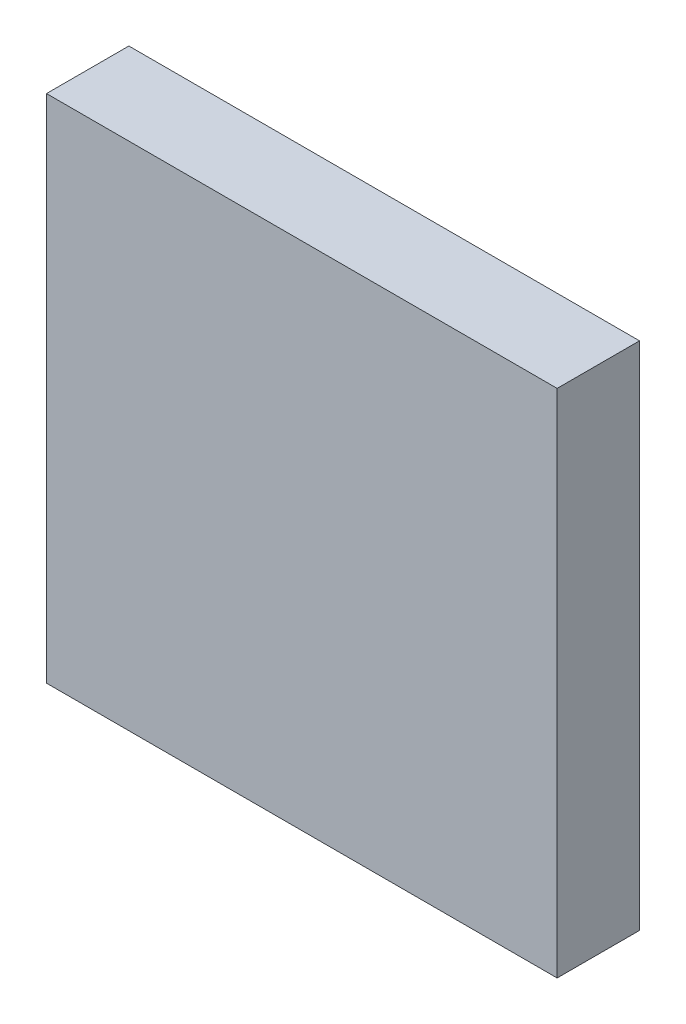
SolidWorks part; units mm, degrees
ref_plane "Спереди" through (0, 0, 0) normal (0, 0, 1) x (1, 0, 0)
ref_plane "Сверху" through (0, 0, 0) normal (0, 1, 0) x (1, 0, 0)
ref_plane "Справа" through (0, 0, 0) normal (1, 0, 0) x (0, 0, -1)
sketch "Эскиз5" plane through (0, 0, 0) normal (0, 0, 1) x (1, 0, 0)
  line L1 (-31, -31) -> (31, -31)
  line L2 (-31, -31) -> (-31, 31)
  line L3 (-31, 31) -> (31, 31)
  line L4 (31, -31) -> (31, 31)
  line L5 (-31, -31) -> (31, 31) construction
  line L6 (-31, 31) -> (31, -31) construction
  point P0 (0, 0)
extrude "Бобышка-Вытянуть2" add sketch "Эскиз5" along normal blind 10 contours L2 L3 L4 L1
sketch "Эскиз13" plane through (0, 0, 10) normal (0, 0, 1) x (1, 0, 0)
  line L0 (-8.5, 3.8388) -> (-8.5, -2.9703)
  line L1 (8.5, -2.9278) -> (8.5, 3.8388)
  spline S0 degree 3 poles (-3.7602, -6.2881) (-4.1456, -5.7125) (-4.7609, -5.3316) (-5.448, -5.2431) knots 0 0 0 0 0.333333 0.333333 0.333333 0.333333
  spline S1 degree 3 poles (-5.448, -5.2431) (-6.135, -5.1547) (-6.8268, -5.3675) (-7.3454, -5.8267) knots 0.333333 0.333333 0.333333 0.333333 1 1 1 1
  spline S2 degree 3 poles (-8.2703, 4.2595) (-8.4134, 4.1675) (-8.5, 4.009) (-8.5, 3.8388) knots 0 0 0 0 1 1 1 1
  spline S3 degree 3 poles (8.2703, 4.2595) (3.2319, 7.4966) (-3.2319, 7.4966) (-8.2703, 4.2595) knots 0 0 0 0 1 1 1 1
  spline S4 degree 3 poles (8.5, 3.8388) (8.5, 4.009) (8.4134, 4.1675) (8.2703, 4.2595) knots 0 0 0 0 1 1 1 1
  spline S5 degree 3 poles (-8.9672, -4.0581) (-8.6689, -3.7749) (-8.5, -3.3816) (-8.5, -2.9703) knots 0 0 0 0 1 1 1 1
  spline S6 degree 3 poles (-8.9672, -4.0581) (-9.4419, -4.5088) (-9.4678, -5.2568) (-9.0253, -5.7393) knots 0 0 0 0 0.333333 0.333333 0.333333 0.333333
  spline S7 degree 3 poles (-9.0253, -5.7393) (-8.5829, -6.2218) (-7.8355, -6.2607) (-7.3454, -5.8267) knots 0.333333 0.333333 0.333333 0.333333 1 1 1 1
  spline S8 degree 3 poles (8.5, -2.9278) (8.5, -3.3579) (8.6732, -3.77) (8.9805, -4.0709) knots 0 0 0 0 1 1 1 1
  spline S9 degree 3 poles (7.6987, -6.0438) (6.4648, -5.5547) (5.0779, -5.6352) (3.9089, -6.2639) knots 0 0 0 0 1 1 1 1
  spline S10 degree 3 poles (7.6987, -6.0438) (8.2299, -6.2544) (8.8358, -6.0612) (9.1472, -5.5821) knots 0 0 0 0 0.333333 0.333333 0.333333 0.333333
  spline S11 degree 3 poles (9.1472, -5.5821) (9.4585, -5.1029) (9.3888, -4.4707) (8.9805, -4.0709) knots 0.333333 0.333333 0.333333 0.333333 1 1 1 1
  spline S12 degree 3 poles (3.1792, -6.3186) (1.2825, -5.6394) (-0.8063, -5.741) (-2.6281, -6.6012) knots 0 0 0 0 1 1 1 1
  spline S13 degree 3 poles (-3.7602, -6.2881) (-3.5123, -6.6582) (-3.0309, -6.7914) (-2.6281, -6.6012) knots 0 0 0 0 1 1 1 1
  spline S14 degree 3 poles (3.1792, -6.3186) (3.4192, -6.4045) (3.6844, -6.3847) (3.9089, -6.2639) knots 0 0 0 0 1 1 1 1
sketch "Эскиз15" plane through (0, 0, 10) normal (0, 0, 1) x (1, 0, 0)
  line L0 (-8.5, 3.8389) -> (-8.5, -2.9702)
  line L1 (8.5, -2.9277) -> (8.5, 3.8389)
  line L2 (-12.5, -12.5) -> (12.5, -12.5)
  line L3 (12.5, -12.5) -> (12.5, 12.5)
  line L4 (12.5, 12.5) -> (-12.5, 12.5)
  line L5 (-12.5, 12.5) -> (-12.5, -12.5)
  spline S0 degree 3 poles (8, 2.6874) (8, 2.9636) (7.7761, 3.1874) (7.5, 3.1874) knots 0 0 0 0 0.2 0.2 0.2 0.2
  spline S1 degree 3 poles (7.5, 3.1874) (7.2239, 3.1874) (7, 2.9636) (7, 2.6874) knots 0.2 0.2 0.2 0.2 0.4 0.4 0.4 0.4
  spline S2 degree 3 poles (7, 2.6874) (7, 2.4113) (7.2239, 2.1874) (7.5, 2.1874) knots 0.4 0.4 0.4 0.4 0.6 0.6 0.6 0.6
  spline S3 degree 3 poles (7.5, 2.1874) (7.7761, 2.1874) (8, 2.4113) (8, 2.6874) knots 0.6 0.6 0.6 0.6 1 1 1 1
  spline S4 degree 3 poles (-4.6079, 1.1218) (-4.6079, 1.6188) (-5.0108, 2.0218) (-5.5079, 2.0218) knots 0 0 0 0 0.2 0.2 0.2 0.2
  spline S5 degree 3 poles (-5.5079, 2.0218) (-6.0049, 2.0218) (-6.4079, 1.6188) (-6.4079, 1.1218) knots 0.2 0.2 0.2 0.2 0.4 0.4 0.4 0.4
  spline S6 degree 3 poles (-6.4079, 1.1218) (-6.4079, 0.6247) (-6.0049, 0.2218) (-5.5079, 0.2218) knots 0.4 0.4 0.4 0.4 0.6 0.6 0.6 0.6
  spline S7 degree 3 poles (-5.5079, 0.2218) (-5.0108, 0.2218) (-4.6079, 0.6247) (-4.6079, 1.1218) knots 0.6 0.6 0.6 0.6 1 1 1 1
  spline S8 degree 3 poles (7.0549, -0.2908) (7.0549, 0.2063) (6.652, 0.6092) (6.1549, 0.6092) knots 0 0 0 0 0.2 0.2 0.2 0.2
  spline S9 degree 3 poles (6.1549, 0.6092) (5.6579, 0.6092) (5.2549, 0.2063) (5.2549, -0.2908) knots 0.2 0.2 0.2 0.2 0.4 0.4 0.4 0.4
  spline S10 degree 3 poles (5.2549, -0.2908) (5.2549, -0.7878) (5.6579, -1.1908) (6.1549, -1.1908) knots 0.4 0.4 0.4 0.4 0.6 0.6 0.6 0.6
  spline S11 degree 3 poles (6.1549, -1.1908) (6.652, -1.1908) (7.0549, -0.7878) (7.0549, -0.2908) knots 0.6 0.6 0.6 0.6 1 1 1 1
  spline S12 degree 3 poles (-7, 2.6874) (-7, 2.9636) (-7.2239, 3.1874) (-7.5, 3.1874) knots 0 0 0 0 0.2 0.2 0.2 0.2
  spline S13 degree 3 poles (-7.5, 3.1874) (-7.7761, 3.1874) (-8, 2.9636) (-8, 2.6874) knots 0.2 0.2 0.2 0.2 0.4 0.4 0.4 0.4
  spline S14 degree 3 poles (-8, 2.6874) (-8, 2.4113) (-7.7761, 2.1874) (-7.5, 2.1874) knots 0.4 0.4 0.4 0.4 0.6 0.6 0.6 0.6
  spline S15 degree 3 poles (-7.5, 2.1874) (-7.2239, 2.1874) (-7, 2.4113) (-7, 2.6874) knots 0.6 0.6 0.6 0.6 1 1 1 1
  spline S16 degree 3 poles (-7.5909, -4.9282) (-7.5909, -4.6244) (-7.8371, -4.3782) (-8.1409, -4.3782) knots 0 0 0 0 0.2 0.2 0.2 0.2
  spline S17 degree 3 poles (-8.1409, -4.3782) (-8.4447, -4.3782) (-8.6909, -4.6244) (-8.6909, -4.9282) knots 0.2 0.2 0.2 0.2 0.4 0.4 0.4 0.4
  spline S18 degree 3 poles (-8.6909, -4.9282) (-8.6909, -5.2319) (-8.4447, -5.4782) (-8.1409, -5.4782) knots 0.4 0.4 0.4 0.4 0.6 0.6 0.6 0.6
  spline S19 degree 3 poles (-8.1409, -5.4782) (-7.8371, -5.4782) (-7.5909, -5.2319) (-7.5909, -4.9282) knots 0.6 0.6 0.6 0.6 1 1 1 1
  spline S20 degree 3 poles (8.6909, -4.9282) (8.6909, -4.6244) (8.4447, -4.3782) (8.1409, -4.3782) knots 0 0 0 0 0.2 0.2 0.2 0.2
  spline S21 degree 3 poles (8.1409, -4.3782) (7.8371, -4.3782) (7.5909, -4.6244) (7.5909, -4.9282) knots 0.2 0.2 0.2 0.2 0.4 0.4 0.4 0.4
  spline S22 degree 3 poles (7.5909, -4.9282) (7.5909, -5.2319) (7.8371, -5.4782) (8.1409, -5.4782) knots 0.4 0.4 0.4 0.4 0.6 0.6 0.6 0.6
  spline S23 degree 3 poles (8.1409, -5.4782) (8.4447, -5.4782) (8.6909, -5.2319) (8.6909, -4.9282) knots 0.6 0.6 0.6 0.6 1 1 1 1
  spline S24 degree 3 poles (3.9826, -5.4712) (3.9826, -5.195) (3.7587, -4.9712) (3.4826, -4.9712) knots 0 0 0 0 0.2 0.2 0.2 0.2
  spline S25 degree 3 poles (3.4826, -4.9712) (3.2064, -4.9712) (2.9826, -5.195) (2.9826, -5.4712) knots 0.2 0.2 0.2 0.2 0.4 0.4 0.4 0.4
  spline S26 degree 3 poles (2.9826, -5.4712) (2.9826, -5.7473) (3.2064, -5.9712) (3.4826, -5.9712) knots 0.4 0.4 0.4 0.4 0.6 0.6 0.6 0.6
  spline S27 degree 3 poles (3.4826, -5.9712) (3.7587, -5.9712) (3.9826, -5.7473) (3.9826, -5.4712) knots 0.6 0.6 0.6 0.6 1 1 1 1
  spline S28 degree 3 poles (-2.5123, -5.7872) (-2.5123, -5.5111) (-2.7362, -5.2872) (-3.0123, -5.2872) knots 0 0 0 0 0.2 0.2 0.2 0.2
  spline S29 degree 3 poles (-3.0123, -5.2872) (-3.2885, -5.2872) (-3.5123, -5.5111) (-3.5123, -5.7872) knots 0.2 0.2 0.2 0.2 0.4 0.4 0.4 0.4
  spline S30 degree 3 poles (-3.5123, -5.7872) (-3.5123, -6.0634) (-3.2885, -6.2872) (-3.0123, -6.2872) knots 0.4 0.4 0.4 0.4 0.6 0.6 0.6 0.6
  spline S31 degree 3 poles (-3.0123, -6.2872) (-2.7362, -6.2872) (-2.5123, -6.0634) (-2.5123, -5.7872) knots 0.6 0.6 0.6 0.6 1 1 1 1
  spline S32 degree 3 poles (6.6049, -0.2908) (6.6049, -0.0422) (6.4034, 0.1592) (6.1549, 0.1592) knots 0 0 0 0 0.2 0.2 0.2 0.2
  spline S33 degree 3 poles (6.1549, 0.1592) (5.9064, 0.1592) (5.7049, -0.0422) (5.7049, -0.2908) knots 0.2 0.2 0.2 0.2 0.4 0.4 0.4 0.4
  spline S34 degree 3 poles (5.7049, -0.2908) (5.7049, -0.5393) (5.9064, -0.7408) (6.1549, -0.7408) knots 0.4 0.4 0.4 0.4 0.6 0.6 0.6 0.6
  spline S35 degree 3 poles (6.1549, -0.7408) (6.4034, -0.7408) (6.6049, -0.5393) (6.6049, -0.2908) knots 0.6 0.6 0.6 0.6 1 1 1 1
  spline S36 degree 3 poles (-5.0579, 1.1218) (-5.0579, 1.3703) (-5.2594, 1.5718) (-5.5079, 1.5718) knots 0 0 0 0 0.2 0.2 0.2 0.2
  spline S37 degree 3 poles (-5.5079, 1.5718) (-5.7564, 1.5718) (-5.9579, 1.3703) (-5.9579, 1.1218) knots 0.2 0.2 0.2 0.2 0.4 0.4 0.4 0.4
  spline S38 degree 3 poles (-5.9579, 1.1218) (-5.9579, 0.8733) (-5.7564, 0.6718) (-5.5079, 0.6718) knots 0.4 0.4 0.4 0.4 0.6 0.6 0.6 0.6
  spline S39 degree 3 poles (-5.5079, 0.6718) (-5.2594, 0.6718) (-5.0579, 0.8733) (-5.0579, 1.1218) knots 0.6 0.6 0.6 0.6 1 1 1 1
  spline S40 degree 3 poles (5.7898, -5.6368) (5.8728, -5.6949) (5.9715, -5.7264) (6.0728, -5.7271) knots 0 0 0 0 1 1 1 1
  spline S41 degree 3 poles (-5.4083, -5.2485) (-5.2964, -5.2648) (-5.1822, -5.2427) (-5.0845, -5.1857) knots 0 0 0 0 1 1 1 1
  spline S42 degree 3 poles (-3.7602, -6.288) (-4.1456, -5.7124) (-4.7609, -5.3315) (-5.448, -5.243) knots 0 0 0 0 0.333333 0.333333 0.333333 0.333333
  spline S43 degree 3 poles (-5.448, -5.243) (-6.135, -5.1546) (-6.8268, -5.3674) (-7.3454, -5.8266) knots 0.333333 0.333333 0.333333 0.333333 1 1 1 1
  spline S44 degree 3 poles (-8.2703, 4.2596) (-8.4134, 4.1676) (-8.5, 4.0091) (-8.5, 3.8389) knots 0 0 0 0 1 1 1 1
  spline S45 degree 3 poles (8.2703, 4.2596) (3.2319, 7.4967) (-3.2319, 7.4967) (-8.2703, 4.2596) knots 0 0 0 0 1 1 1 1
  spline S46 degree 3 poles (8.5, 3.8389) (8.5, 4.0091) (8.4134, 4.1676) (8.2703, 4.2596) knots 0 0 0 0 1 1 1 1
  spline S47 degree 3 poles (5.7898, -5.6368) (2.563, -3.3793) (-1.6818, -3.2032) (-5.0845, -5.1857) knots 0 0 0 0 1 1 1 1
  spline S48 degree 3 poles (-8.9672, -4.058) (-8.6689, -3.7748) (-8.5, -3.3815) (-8.5, -2.9702) knots 0 0 0 0 1 1 1 1
  spline S49 degree 3 poles (-8.9672, -4.058) (-9.4419, -4.5087) (-9.4678, -5.2567) (-9.0253, -5.7392) knots 0 0 0 0 0.333333 0.333333 0.333333 0.333333
  spline S50 degree 3 poles (-9.0253, -5.7392) (-8.5829, -6.2217) (-7.8355, -6.2606) (-7.3454, -5.8266) knots 0.333333 0.333333 0.333333 0.333333 1 1 1 1
  spline S51 degree 3 poles (8.5, -2.9277) (8.5, -3.3578) (8.6732, -3.7699) (8.9805, -4.0708) knots 0 0 0 0 1 1 1 1
  spline S52 degree 3 poles (7.6987, -6.0437) (6.4648, -5.5546) (5.0779, -5.6351) (3.9089, -6.2638) knots 0 0 0 0 1 1 1 1
  spline S53 degree 3 poles (7.6987, -6.0437) (8.2299, -6.2543) (8.8358, -6.0611) (9.1472, -5.582) knots 0 0 0 0 0.333333 0.333333 0.333333 0.333333
  spline S54 degree 3 poles (9.1472, -5.582) (9.4585, -5.1028) (9.3888, -4.4706) (8.9805, -4.0708) knots 0.333333 0.333333 0.333333 0.333333 1 1 1 1
  spline S55 degree 3 poles (3.1792, -6.3185) (1.2825, -5.6393) (-0.8063, -5.7409) (-2.6281, -6.6011) knots 0 0 0 0 1 1 1 1
  spline S56 degree 3 poles (-3.7602, -6.288) (-3.5123, -6.6581) (-3.0309, -6.7913) (-2.6281, -6.6011) knots 0 0 0 0 1 1 1 1
  spline S57 degree 3 poles (3.1792, -6.3185) (3.4192, -6.4044) (3.6844, -6.3846) (3.9089, -6.2638) knots 0 0 0 0 1 1 1 1
sketch "обнижение под перлаж" plane through (0, 0, 10) normal (0, 0, 1) x (1, 0, 0)
  ellipse E0 centre (0, -7.2674) end of major axis (6.1105, -7.2674) minor radius 3.5988
sketch "карман под съем моста" plane through (0, 0, 10) normal (0, 0, 1) x (1, 0, 0)
  line L0 (-13.7619, 0) -> (13.4181, 0) construction
  line L1 (-13.7619, 1) -> (13.4181, 1)
  line L2 (-13.7619, -1) -> (13.4181, -1)
  arc A0 (-13.7619, 1) -> (-13.7619, -1) centre (-13.7619, 0) ccw
  arc A1 (13.4181, -1) -> (13.4181, 1) centre (13.4181, 0) ccw
  point P3 (-0.1719, 0)
sketch "острова" plane through (0, 0, 10) normal (0, 0, 1) x (1, 0, 0)
  spline S0 degree 2 poles (-8.5, -2.0317) (-8.5, -2.5998) (-8.5, -2.9703) knots 0 0 0 1 1 1
  spline S1 degree 3 poles (-5.4691, 5.3435) (-5.4628, 5.5492) (-5.3311, 5.73) (-5.1372, 5.7991) knots 0 0 0 0 1 1 1 1
  spline S2 degree 3 poles (-8.3317, 4.2129) (-8.1698, 4.2866) (-7.9808, 4.2686) (-7.8357, 4.1657) knots 0 0 0 0 1 1 1 1
  spline S3 degree 3 poles (-8.3317, 4.2129) (-8.3126, 4.2298) (-8.2921, 4.2455) (-8.2703, 4.2595) knots 0 0 0 0 1 1 1 1
  spline S4 degree 3 poles (-8.0243, -2.5311) (-8.2907, -2.5182) (-8.5, -2.2984) (-8.5, -2.0317) knots 0 0 0 0 1 1 1 1
  spline S5 degree 3 poles (-8.0243, -2.5311) (-6.7965, -2.5908) (-5.8123, -3.5687) (-5.7445, -4.7961) knots 0 0 0 0 1 1 1 1
  spline S6 degree 3 poles (-5.3331, -5.2608) (-5.5614, -5.2201) (-5.7318, -5.0277) (-5.7445, -4.7961) knots 0 0 0 0 1 1 1 1
  spline S7 degree 3 poles (6.4277, -5.7438) (6.8591, -5.781) (7.2875, -5.8808) (7.6987, -6.0438) knots 0 0 0 0 1 1 1 1
  spline S8 degree 3 poles (6.962, -5.1523) (6.9912, -5.3061) (6.9468, -5.4647) (6.8418, -5.5808) knots 0 0 0 0 0.333333 0.333333 0.333333 0.333333
  spline S9 degree 3 poles (6.8418, -5.5808) (6.7369, -5.697) (6.5837, -5.7573) (6.4277, -5.7438) knots 0.333333 0.333333 0.333333 0.333333 1 1 1 1
  spline S10 degree 3 poles (6.962, -5.1523) (6.898, -4.8155) (6.9811, -4.4674) (7.1904, -4.1958) knots 0 0 0 0 0.333333 0.333333 0.333333 0.333333
  spline S11 degree 3 poles (7.1904, -4.1958) (7.3997, -3.9242) (7.7151, -3.7551) (8.0571, -3.7312) knots 0.333333 0.333333 0.333333 0.333333 1 1 1 1
  spline S12 degree 3 poles (8.5169, -3.1599) (8.5371, -3.2976) (8.499, -3.4375) (8.4117, -3.5459) knots 0 0 0 0 0.333333 0.333333 0.333333 0.333333
  spline S13 degree 3 poles (8.4117, -3.5459) (8.3245, -3.6543) (8.196, -3.7215) (8.0571, -3.7312) knots 0.333333 0.333333 0.333333 0.333333 1 1 1 1
  spline S14 degree 3 poles (8.9805, -4.0709) (8.729, -3.8247) (8.5673, -3.504) (8.5169, -3.1599) knots 0 0 0 0 1 1 1 1
  spline S15 degree 3 poles (8.2703, 4.2595) (8.2921, 4.2455) (8.3126, 4.2298) (8.3317, 4.2129) knots 0 0 0 0 1 1 1 1
  spline S16 degree 3 poles (7.8357, 4.1657) (7.9808, 4.2686) (8.1698, 4.2866) (8.3317, 4.2129) knots 0 0 0 0 1 1 1 1
  spline S17 degree 3 poles (7.8357, 4.1657) (7.3848, 3.8462) (6.7948, 3.8005) (6.3001, 4.0467) knots 0 0 0 0 0.333333 0.333333 0.333333 0.333333
  spline S18 degree 3 poles (6.3001, 4.0467) (5.8054, 4.2929) (5.4861, 4.7912) (5.4691, 5.3435) knots 0.333333 0.333333 0.333333 0.333333 1 1 1 1
  spline S19 degree 3 poles (5.1372, 5.7991) (5.3311, 5.73) (5.4628, 5.5492) (5.4691, 5.3435) knots 0 0 0 0 1 1 1 1
  spline S20 degree 3 poles (-8.2703, 4.2595) (-7.2743, 4.8994) (-6.2227, 5.4129) (-5.1372, 5.7991) knots 0 0 0 0 1 1 1 1
  spline S21 degree 3 poles (5.1372, 5.7991) (6.2227, 5.4129) (7.2744, 4.8994) (8.2703, 4.2595) knots 0 0 0 0 1 1 1 1
  spline S22 degree 3 poles (-7.3454, -5.8267) (-6.8268, -5.3675) (-6.135, -5.1547) (-5.448, -5.2431) knots 0 0 0 0 0.333333 0.333333 0.333333 0.333333
  spline S23 degree 3 poles (-5.448, -5.2431) (-5.4095, -5.2481) (-5.3711, -5.254) (-5.3331, -5.2608) knots 0.333333 0.333333 0.333333 0.333333 1 1 1 1
  spline S24 degree 3 poles (-5.4691, 5.3435) (-5.4861, 4.7912) (-5.8054, 4.2929) (-6.3001, 4.0467) knots 0 0 0 0 0.333333 0.333333 0.333333 0.333333
  spline S25 degree 3 poles (-6.3001, 4.0467) (-6.7948, 3.8005) (-7.3848, 3.8462) (-7.8357, 4.1657) knots 0.333333 0.333333 0.333333 0.333333 1 1 1 1
  spline S26 degree 3 poles (-8.5, -2.9703) (-8.5, -3.3816) (-8.6689, -3.7749) (-8.9672, -4.0581) knots 0 0 0 0 1 1 1 1
  spline S27 degree 3 poles (8.9805, -4.0709) (9.3888, -4.4707) (9.4585, -5.1029) (9.1472, -5.5821) knots 0 0 0 0 0.333333 0.333333 0.333333 0.333333
  spline S28 degree 3 poles (9.1472, -5.5821) (8.8358, -6.0612) (8.2299, -6.2544) (7.6987, -6.0438) knots 0.333333 0.333333 0.333333 0.333333 1 1 1 1
  spline S29 degree 3 poles (-7.3454, -5.8267) (-7.8355, -6.2607) (-8.5829, -6.2218) (-9.0253, -5.7393) knots 0 0 0 0 0.333333 0.333333 0.333333 0.333333
  spline S30 degree 3 poles (-9.0253, -5.7393) (-9.4678, -5.2568) (-9.4419, -4.5088) (-8.9672, -4.0581) knots 0.333333 0.333333 0.333333 0.333333 1 1 1 1
sketch "ПерлажЛицо" plane through (0, 0, 10) normal (0, 0, 1) x (1, 0, 0)
  circle A0 centre (-4.5736, -6.1109) radius 1
  circle A1 centre (-3.6512, -5.6439) radius 1
  circle A2 centre (-2.6818, -5.2842) radius 1
  circle A3 centre (-1.6779, -5.0367) radius 1
  circle A4 centre (-0.6524, -4.9044) radius 1
  circle A5 centre (0.3814, -4.889) radius 1
  circle A6 centre (1.4104, -4.9907) radius 1
  circle A7 centre (2.4212, -5.2083) radius 1
  circle A8 centre (3.4009, -5.5389) radius 1
  circle A9 centre (4.3368, -5.9783) radius 1
  circle A10 centre (5.2171, -6.5208) radius 1
  circle A11 centre (-3.6512, -6.6924) radius 1
  circle A12 centre (-2.6665, -6.3218) radius 1
  circle A13 centre (-1.6453, -6.0688) radius 1
  circle A14 centre (-0.6015, -5.937) radius 1
  circle A15 centre (0.4506, -5.9282) radius 1
  circle A16 centre (1.4965, -6.0424) radius 1
  circle A17 centre (2.5218, -6.2781) radius 1
  circle A18 centre (3.5126, -6.6321) radius 1
  point P27 (0, -14)
  point P45 (0, -14.9)
  dimension "D1" = 11
  dimension "D2" = 8
sketch "Эскиз16" plane through (0, 0, 10) normal (0, 0, 1) x (1, 0, 0)
  circle A0 centre (0, 0) radius 31
